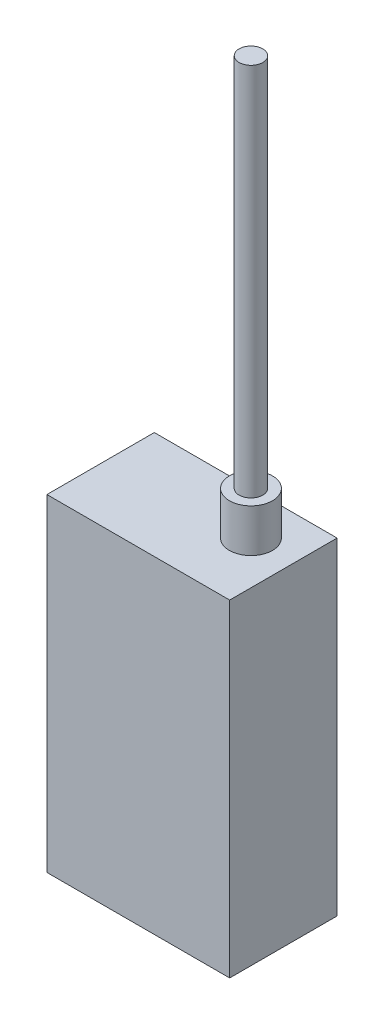
SolidWorks part; units mm, degrees
ref_plane "Front Plane" through (0, 0, 0) normal (0, 0, 1) x (1, 0, 0)
ref_plane "Top Plane" through (0, 0, 0) normal (0, 1, 0) x (1, 0, 0)
ref_plane "Right Plane" through (0, 0, 0) normal (1, 0, 0) x (0, 0, -1)
sketch "Sketch1" plane through (0, 0, 0) normal (0, 0, 1) x (1, 0, 0)
  line L1 (26.9494, -48.26) -> (-26.9494, -48.26)
  line L2 (26.9494, -48.26) -> (26.9494, 48.26)
  line L3 (26.9494, 48.26) -> (-26.9494, 48.26)
  line L4 (-26.9494, -48.26) -> (-26.9494, 48.26)
  line L5 (26.9494, -48.26) -> (-26.9494, 48.26) construction
  line L6 (26.9494, 48.26) -> (-26.9494, -48.26) construction
  point P0 (0, 0)
  dimension "D1" = 53.8988
  dimension "D2" = 96.52
extrude "Boss-Extrude1" add sketch "Sketch1" along normal blind 31.6738
sketch "Sketch2" plane through (0, 48.26, 0) normal (0, 1, 0) x (1, 0, 0)
  line L2 (26.9494, 0) -> (-26.9494, 0) construction
  circle A0 centre (14.2494, -12.7) radius 6.35
  dimension "D1" = 12.7
extrude "Boss-Extrude2" add sketch "Sketch2" along normal blind 12.7 contours A0
sketch "Sketch3" plane through (0, 60.96, 0) normal (0, 1, 0) x (1, 0, 0)
  circle A0 centre (14.2494, -12.7) radius 3.4925
extrude "Boss-Extrude3" add sketch "Sketch3" along normal blind 110.49
